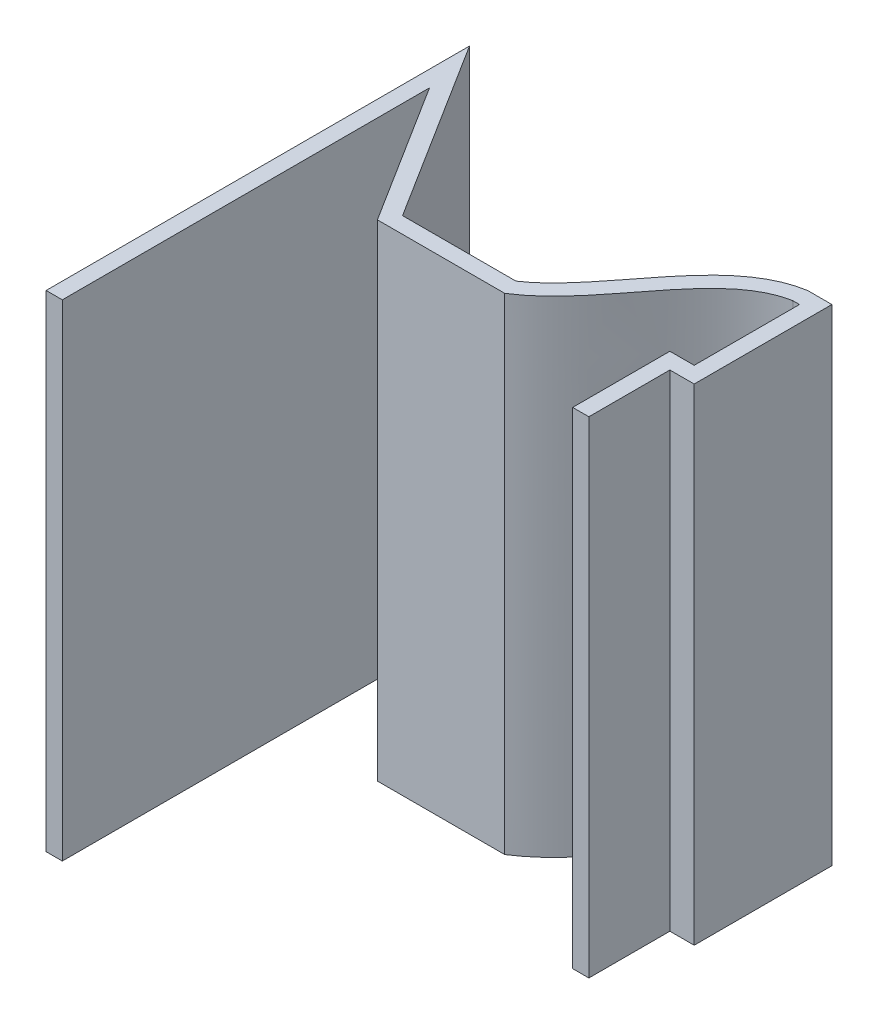
SolidWorks part; units mm, degrees
ref_plane "Front Plane" through (0, 0, 0) normal (0, 0, 1) x (1, 0, 0)
ref_plane "Top Plane" through (0, 0, 0) normal (0, 1, 0) x (1, 0, 0)
ref_plane "Right Plane" through (0, 0, 0) normal (1, 0, 0) x (0, 0, -1)
sketch "Sketch1" plane through (0, 0, 0) normal (0, 1, 0) x (1, 0, 0)
  line L3 (3, 47) -> (3, 30)
  line L4 (3, 30) -> (0, 30)
  line L5 (0, 0) -> (0, 30)
  line L6 (0, 47) -> (3, 47)
  line L9 (-33, 30) -> (-19, 30)
  line L23 (-47, 52.2684) -> (-33, 30)
  line L25 (-45, 0) -> (-45, 45.3295)
  line L26 (-45, 45.3295) -> (-34.105, 28)
  line L27 (-34.105, 28) -> (-18.3864, 28)
  line L28 (-47, 0) -> (-47, 52.2684)
  line L29 (0.1761, 45) -> (1, 45)
  line L30 (1, 45) -> (1, 32)
  line L31 (1, 32) -> (-2, 32)
  line L32 (-2, 0) -> (-2, 32)
  line L33 (-47, 0) -> (-45, 0)
  line L34 (-2, 0) -> (0, 0)
  spline S0 degree 3 poles (0, 47) (-8.7358, 45.5223) (-12.4112, 34.4627) (-19, 30) knots 0 0 0 0 1 1 1 1
  spline S1 degree 1 poles (0.1761, 45) (-18.3864, 28) knots 0 0 1 1 construction
  spline S2 degree 3 poles (-18.3864, 28) (-18.2816, 28.071) (-18.076, 28.2106) (-17.632, 28.509) (-16.7888, 29.1278) (-15.2661, 30.4367) (-13.2818, 32.5788) (-11.1163, 35.3224) (-8.328, 38.9716) (-4.7963, 42.9893) (-1.6054, 44.6674) (0.1761, 45) knots 0.007316 0.007316 0.007316 0.007316 0.023228 0.03914 0.070965 0.134614 0.261912 0.38921 0.516508 0.771104 1.025701 1.025701 1.025701 1.025701
  point P1 (-52, 0)
extrude "Boss-Extrude12" add sketch "Sketch1" along normal blind 60
sketch "Sketch2" plane through (0, 0, -30) normal (0, 0, -1) x (-1, 0, 0)
  line L0 (19, 60) -> (33, 60) construction
  line L1 (19, 60) -> (19, 0) construction
  line L2 (33, 0) -> (19, 0)
  line L3 (33, 0) -> (33, 2.424)
  line L5 (19, 0) -> (19, 2.424)
  arc A0 (19, 2.424) -> (33, 2.424) centre (26, 60) ccw
extrude "Boss-Extrude13" add sketch "Sketch2" along normal blind 8
sketch "Sketch3" plane through (0, 0, 0) normal (1, 0, 0) x (0, 0, -1)
  line L0 (0, 0) -> (30, 0) construction
  line L1 (0, 60) -> (20, 60)
  line L2 (0, 60) -> (0, 0)
  line L3 (0, 0) -> (20, 0)
  line L4 (20, 60) -> (20, 0)
extrude "Cut-Extrude1" cut sketch "Sketch3" against normal blind 10
